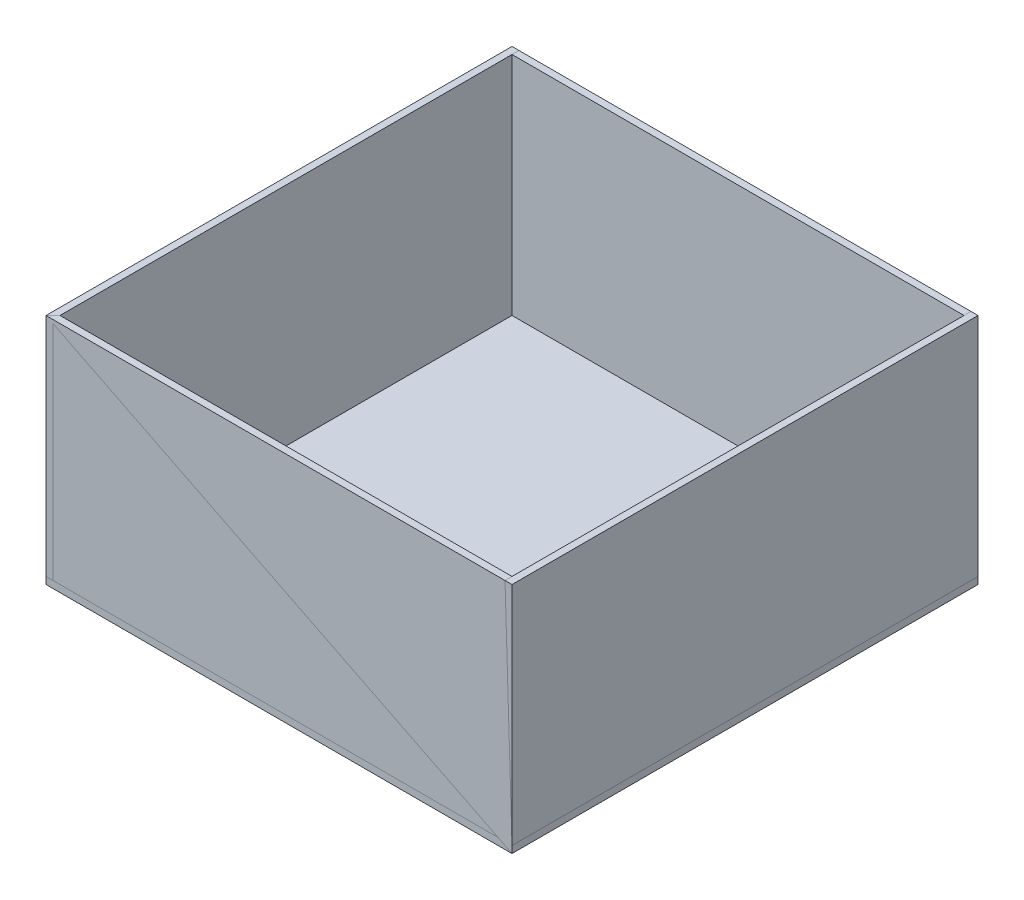
SolidWorks part; units mm, degrees
other "COLL.BOX-Boss-Extrude2"
other "COLL.BOX-Boss-Extrude3[1]"
other "COLL.BOX-Boss-Extrude3[2]"
other "COLL.BOX-Boss-Extrude4[1]"
other "COLL.BOX-Boss-Extrude4[2]"
material "ABS"
ref_plane "Front Plane" through (0, 0, 0) normal (0, 0, 1) x (1, 0, 0)
ref_plane "Top Plane" through (0, 0, 0) normal (0, 1, 0) x (1, 0, 0)
ref_plane "Right Plane" through (0, 0, 0) normal (1, 0, 0) x (0, 0, -1)
sketch "Sketch1" plane through (0, 0, 0) normal (0, 1, 0) x (1, 0, 0)
  line L0 (-100, 100) -> (-100, -100)
  line L1 (-100, -100) -> (100, -100)
  line L2 (100, -100) -> (100, 100)
  line L3 (100, 100) -> (-100, 100)
  point P4 (-100, 0)
  point P6 (0, 100)
  dimension "D1" = 200
extrude "Boss-Extrude1" add sketch "Sketch1" along normal blind 100
sketch "Sketch2" plane through (0, 100, 0) normal (0, 1, 0) x (1, 0, 0)
  line L0 (97, 97) -> (-97, 97)
  line L1 (-97, 97) -> (-97, -97)
  line L2 (-97, -97) -> (97, -97)
  line L3 (97, -97) -> (97, 97)
  line L4 (100, 100) -> (-100, 100)
  line L5 (-100, 100) -> (-100, -100)
  line L6 (-100, -100) -> (100, -100)
  line L7 (100, -100) -> (100, 100)
  line L8 (100, 100) -> (-100, 100) construction
  line L9 (-100, 100) -> (-100, -100) construction
  line L10 (-100, -100) -> (100, -100) construction
  line L11 (100, -100) -> (100, 100) construction
  dimension "D1" = 0
  dimension "D2" = 3
extrude "Cut-Extrude1" cut sketch "Sketch2" against normal blind 97
sketch "Sketch3" plane through (0, 0, 0) normal (0, -1, 0) x (1, 0, 0)
  line L4 (-100, -100) -> (100, -100)
  line L5 (100, -100) -> (100, 100)
  line L6 (100, 100) -> (-100, 100)
  line L7 (-100, 100) -> (-100, -100)
  line L8 (-100, -100) -> (100, -100)
  line L9 (100, -100) -> (100, 100)
  line L10 (100, 100) -> (-100, 100)
  line L11 (-100, 100) -> (-100, -100)
  dimension "D1" = 0
extrude "Boss-Extrude2" add sketch "Sketch3" against normal up to surface (3 mm away) separate body up to face at (0, 3, 0)
sketch "Sketch4" plane through (0, 3, 0) normal (0, 1, 0) x (1, 0, 0)
  line L0 (-100, -100) -> (100, -100) construction
  line L1 (-100, 100) -> (-97, 100)
  line L2 (-100, 100) -> (-100, -100)
  line L3 (-100, -100) -> (-97, -100)
  line L4 (-97, 100) -> (-97, -100)
  line L5 (-97, 97) -> (-97, -97) construction
  line L6 (97, -97) -> (97, 97) construction
  line L7 (100, 100) -> (97, 100)
  line L8 (100, 100) -> (100, -100)
  line L9 (100, -100) -> (97, -100)
  line L10 (97, 100) -> (97, -100)
extrude "Boss-Extrude3" add sketch "Sketch4" along normal up to surface (97 mm away) separate body up to face at (0, 100, 0)
sketch "Sketch5" plane through (0, 3, 0) normal (0, 1, 0) x (1, 0, 0)
  line L1 (-97, 100) -> (97, 100)
  line L2 (-97, 100) -> (-97, 97)
  line L3 (-97, 97) -> (97, 97)
  line L4 (97, 100) -> (97, 97)
  line L5 (-97, -100) -> (97, -100)
  line L6 (-97, -100) -> (-97, -97)
  line L7 (-97, -97) -> (97, -97)
  line L8 (97, -100) -> (97, -97)
extrude "Boss-Extrude4" add sketch "Sketch5" along normal up to surface (97 mm away) separate body up to face at (-98.5, 100, 0)
